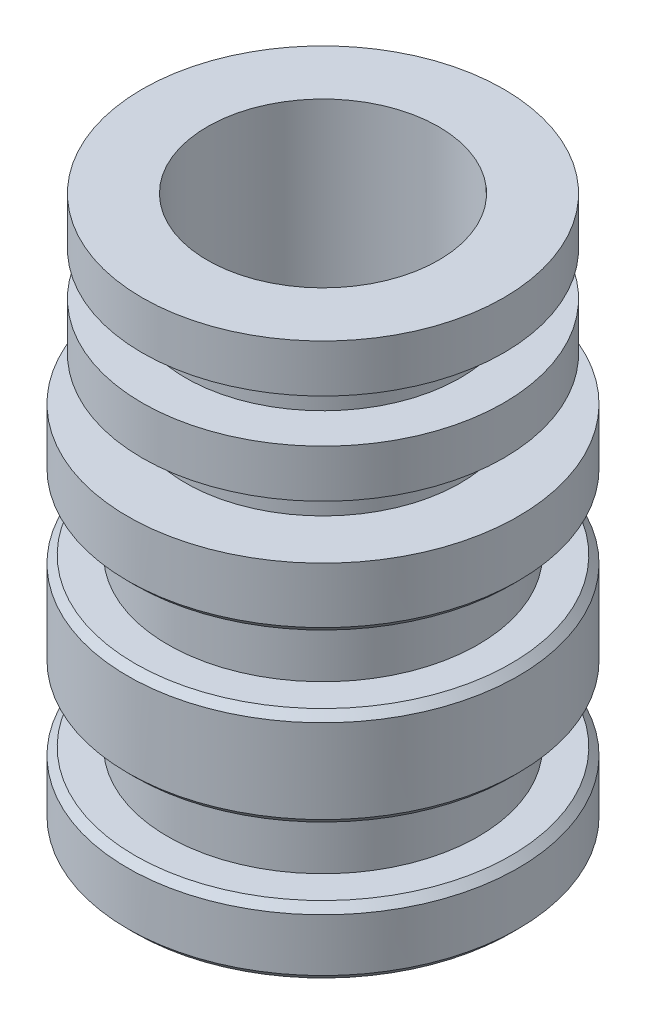
SolidWorks part; units mm, degrees
material "AISI 316 Barre d'acier inoxydable recuit (SS)"
ref_plane "Plan de face" through (0, 0, 0) normal (0, 0, 1) x (1, 0, 0)
ref_plane "Plan de dessus" through (0, 0, 0) normal (0, 1, 0) x (1, 0, 0)
ref_plane "Plan de droite" through (0, 0, 0) normal (1, 0, 0) x (0, 0, -1)
sketch "Esquisse1" plane through (0, 0, 0) normal (0, 0, 1) x (1, 0, 0)
  line L0 (0, -29.1154) -> (0, 30.7029) construction
  line L4 (-2, 14.84) -> (-2, -6.16) construction
  line L5 (-2, -6.16) -> (0, -6.16) construction
  line L9 (0, 0) -> (-13.5, 0)
  line L10 (-13.5, 0) -> (-13.5, 25.2) construction
  line L11 (-2, 14.84) -> (-8, 20.84) construction
  line L13 (-12.5, 29.0574) -> (-12.5, 31.5) construction
  line L18 (-12.5, 31.5) -> (-12.5, 28.2)
  line L19 (-12.5, 28.2) -> (-9.5, 28.2)
  line L20 (-9.5, 28.2) -> (-9.5, 25.2)
  line L29 (-9.5, 25.2) -> (-12.5, 25.2)
  line L33 (-13.5, 25.2) -> (-12.5, 25.2)
  line L35 (-13.5, 25.2) -> (-13.5, 20.84)
  line L36 (-13.5, 16.14) -> (-13.5, 9.34)
  line L37 (-13.5, 4.64) -> (-13.5, 0)
  line L39 (-2, 14.84) -> (-2, -6.16) construction
  line L42 (-8, 20.84) -> (-8, 8)
  line L43 (-8, 8) -> (0, 8)
  line L44 (-13.5, 20.84) -> (-10.73, 20.84)
  line L45 (-10.73, 20.84) -> (-10.73, 16.14)
  line L46 (-10.73, 16.14) -> (-13.5, 16.14)
  line L47 (-13.5, 9.34) -> (-10.73, 9.34)
  line L48 (-10.73, 9.34) -> (-10.73, 4.64)
  line L49 (-10.73, 4.64) -> (-13.5, 4.64)
  line L50 (0, 8) -> (0, 0)
  line L51 (-12.5, 31.5) -> (-9.5, 31.5)
  line L52 (-9.5, 31.5) -> (-9.5, 34.5)
  line L53 (-9.5, 34.5) -> (-12.5, 34.5)
  line L54 (-12.5, 34.5) -> (-12.5, 37.8)
  line L55 (-12.5, 37.8) -> (-8, 37.8)
  line L56 (-8, 37.8) -> (-8, 20.84)
  point P3 (-13, 25.2)
  dimension "D5" = 4.7
  dimension "D12" = 25.2
  dimension "D7" = 10.73
  dimension "D1" = 2
  dimension "D2" = 13.5
  dimension "D3" = 8
  dimension "D4" = 1
  dimension "D6" = 6.8
  dimension "D8" = 4.36
  dimension "D9" = 4.64
  dimension "D10" = 3
  dimension "45" = 45
  dimension "D11" = 8
  dimension "D13" = 21
  dimension "D14" = 9.5
  dimension "D15" = 3
  dimension "D16" = 12.5
  dimension "D17" = 3.3
revolve "Révolution1" add sketch "Esquisse1" angle 360 about L0
sketch "Esquisse4" plane through (0, 0, 0) normal (0, -1, 0) x (1, 0, 0)
  circle A0 centre (0, 0) radius 3
  dimension "D1" = 6
extrude "Enlèv. mat.-Extru.3" cut sketch "Esquisse4" against normal through all
chamfer "Chanfrein4" distance 1 angle 45 2 edges at (0, 8, -3) (0, 0, -3)
chamfer "Chanfrein3" distance 0.5 angle 45 5 edges at (0, 0, -13.5) (0, 20.84, -13.5) (0, 16.14, -13.5) (0, 9.34, -13.5) (0, 4.64, -13.5)
sketch "Esquisse5" plane through (0, 0, 0) normal (0, 0, 1) x (1, 0, 0)
  line L0 (0, 0) -> (0, -12.5671) construction
  line L1 (36, -36) -> (50.3531, -36) construction
  arc A0 (0, 0) -> (36, -36) centre (36, 0) ccw construction
  dimension "D2" = 36
equation "\"1à.00mm\"=12"
